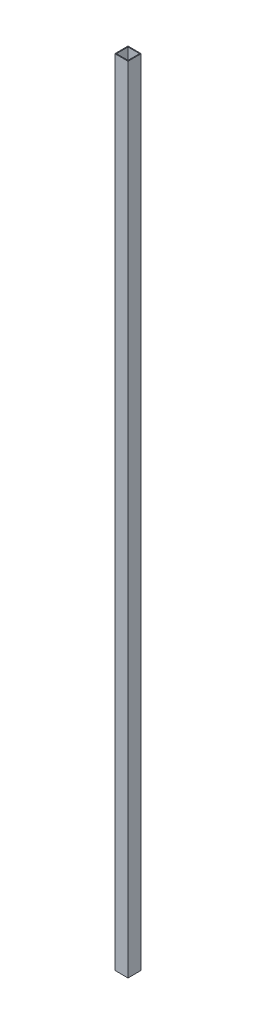
SolidWorks part; units mm, degrees
ref_plane "Front Plane" through (0, 0, 0) normal (0, 0, 1) x (1, 0, 0)
ref_plane "Top Plane" through (0, 0, 0) normal (0, 1, 0) x (1, 0, 0)
ref_plane "Right Plane" through (0, 0, 0) normal (1, 0, 0) x (0, 0, -1)
sketch "Sketch1" plane through (0, 0, 0) normal (0, 1, 0) x (1, 0, 0)
  line L1 (-25.4, 25.4) -> (25.4, 25.4)
  line L2 (-25.4, 25.4) -> (-25.4, -25.4)
  line L3 (-25.4, -25.4) -> (25.4, -25.4)
  line L4 (25.4, 25.4) -> (25.4, -25.4)
  line L5 (-25.4, 25.4) -> (25.4, -25.4) construction
  line L6 (-25.4, -25.4) -> (25.4, 25.4) construction
  line L7 (-22.225, 22.225) -> (22.225, 22.225)
  line L8 (-22.225, 22.225) -> (-22.225, -22.225)
  line L9 (-22.225, -22.225) -> (22.225, -22.225)
  line L10 (22.225, 22.225) -> (22.225, -22.225)
  line L11 (-22.225, 22.225) -> (22.225, -22.225) construction
  line L12 (-22.225, -22.225) -> (22.225, 22.225) construction
  point P0 (0, 0)
  point P6 (0, 0)
  dimension "D1" = 50.8
  dimension "D2" = 3.175
extrude "Boss-Extrude1" add sketch "Sketch1" along normal blind 3048
